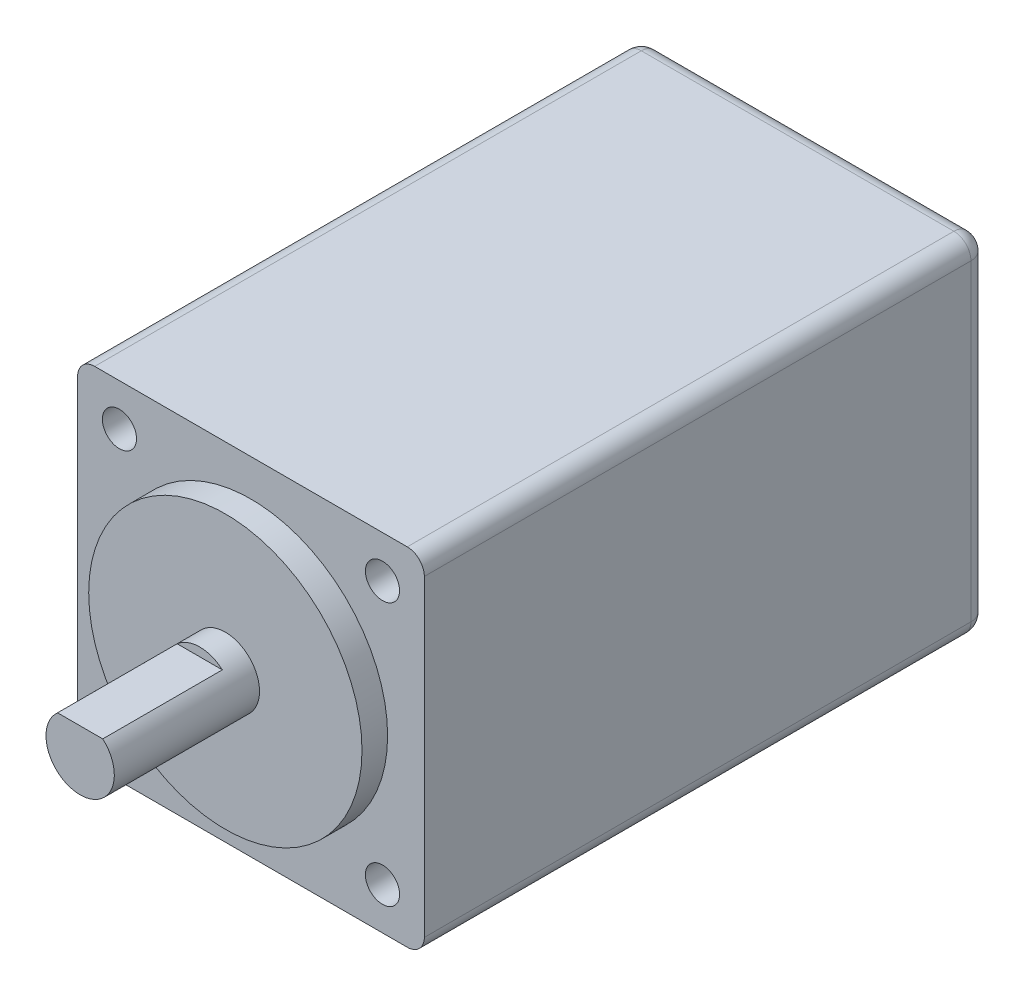
SolidWorks part; units mm, degrees
ref_plane "Front Plane" through (0, 0, 0) normal (0, 0, 1) x (1, 0, 0)
ref_plane "Top Plane" through (0, 0, 0) normal (0, 1, 0) x (1, 0, 0)
ref_plane "Right Plane" through (0, 0, 0) normal (1, 0, 0) x (0, 0, -1)
sketch "Sketch1" plane through (0, 0, 0) normal (0, 0, 1) x (1, 0, 0)
  line L1 (-10.15, -10.15) -> (10.15, -10.15)
  line L2 (-10.15, -10.15) -> (-10.15, 10.15)
  line L3 (-10.15, 10.15) -> (10.15, 10.15)
  line L4 (10.15, -10.15) -> (10.15, 10.15)
  line L5 (-10.15, -10.15) -> (10.15, 10.15) construction
  line L6 (-10.15, 10.15) -> (10.15, -10.15) construction
  point P0 (0, 0)
  dimension "D1" = 20.3
  dimension "D2" = 20.3
extrude "Boss-Extrude1" add sketch "Sketch1" along normal blind 33
sketch "Sketch2" plane through (0, 0, 33) normal (0, 0, 1) x (1, 0, 0)
  circle A0 centre (0, 0) radius 8
  dimension "D1" = 16
extrude "Boss-Extrude2" add sketch "Sketch2" along normal blind 1.5
sketch "Sketch3" plane through (0, 0, 34.5) normal (0, 0, 1) x (1, 0, 0)
  circle A0 centre (0, 0) radius 2
  dimension "D1" = 4
extrude "Boss-Extrude3" add sketch "Sketch3" along normal blind 8.5
sketch "Sketch4" plane through (0, 0, 0) normal (1, 0, 0) x (0, 0, -1)
  line L1 (-43, 2) -> (-36, 2)
  line L2 (-43, 2) -> (-43, 1.5)
  line L3 (-43, 1.5) -> (-36, 1.5)
  line L4 (-36, 2) -> (-36, 1.5)
  dimension "D1" = 7
  dimension "D2" = 0.5
extrude "Cut-Extrude1" cut sketch "Sketch4" against normal mid plane 10
sketch "Sketch5" plane through (0, 0, 33) normal (0, 0, 1) x (1, 0, 0)
  line L1 (-7.7, -7.7) -> (7.7, -7.7) construction
  line L2 (-7.7, -7.7) -> (-7.7, 7.7) construction
  line L3 (-7.7, 7.7) -> (7.7, 7.7) construction
  line L4 (7.7, -7.7) -> (7.7, 7.7) construction
  line L5 (-7.7, -7.7) -> (7.7, 7.7) construction
  line L6 (-7.7, 7.7) -> (7.7, -7.7) construction
  circle A0 centre (-7.7, 7.7) radius 1
  circle A1 centre (7.7, 7.7) radius 1
  circle A2 centre (7.7, -7.7) radius 1
  circle A3 centre (-7.7, -7.7) radius 1
  point P0 (0, 0)
  dimension "D3" = 2
  dimension "D1" = 15.4
  dimension "D2" = 15.4
  dimension "D4" = 4
extrude "Cut-Extrude2" cut sketch "Sketch5" against normal blind 2.5
fillet "Fillet1" radius 1 8 edges at (0, 10.15, 0) (-10.15, 0, 0) (0, -10.15, 0) (10.15, 0, 0) (-10.15, -10.15, 16.5) (10.15, -10.15, 16.5) (-10.15, 10.15, 16.5) (10.15, 10.15, 16.5)
